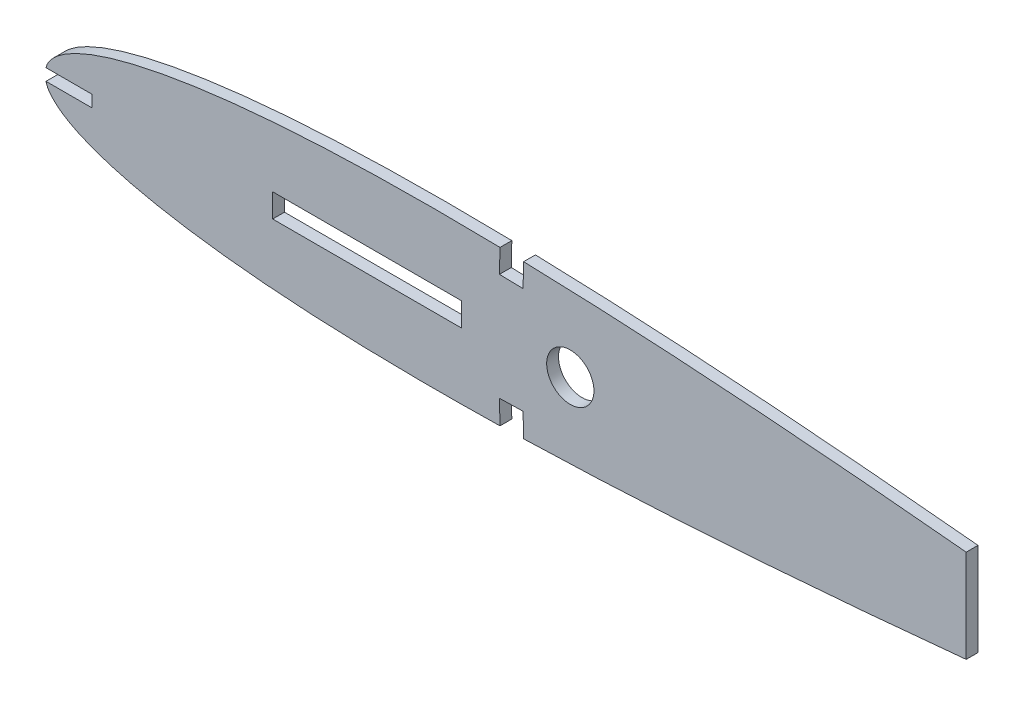
SolidWorks part; units mm, degrees
material "Balsa"
ref_plane "Front Plane" through (0, 0, 0) normal (0, 0, 1) x (1, 0, 0)
ref_plane "Top Plane" through (0, 0, 0) normal (0, 1, 0) x (1, 0, 0)
ref_plane "Right Plane" through (0, 0, 0) normal (1, 0, 0) x (0, 0, -1)
curve "Curve1"
  spline degree 3 poles (318.77, 0, 0) (318.6165, 0.178, 0) (318.1279, 0.7447, 0) (316.4159, 0.5798, 0) (314.0794, 1.1239, 0) (310.6457, 1.4976, 0) (306.3402, 2.1168, 0) (301.1057, 2.7975, 0) (295.0055, 3.5941, 0) (288.0665, 4.472, 0) (280.335, 5.4268, 0) (271.8575, 6.4421, 0) (262.6867, 7.5062, 0) (252.8789, 8.6045, 0) (242.4947, 9.7236, 0) (231.5982, 10.8496, 0) (220.2564, 11.9679, 0) (208.5394, 13.0629, 0) (196.5193, 14.1202, 0) (184.2704, 15.122, 0) (171.8679, 16.0521, 0) (159.3884, 16.8933, 0) (146.9087, 17.6278, 0) (134.5058, 18.2372, 0) (122.2562, 18.7052, 0) (110.2351, 19.0165, 0) (98.5168, 19.156, 0) (87.1732, 19.1125, 0) (76.2743, 18.8777, 0) (65.8873, 18.4456, 0) (56.076, 17.8151, 0) (46.9007, 16.9881, 0) (38.4176, 15.971, 0) (30.6784, 14.7725, 0) (23.7299, 13.4051, 0) (17.6134, 11.8842, 0) (12.3615, 10.2248, 0) (8.0073, 8.4423, 0) (4.5466, 6.5486, 0) (2.0351, 4.5401, 0) (0.333, 2.3682, 0) (0.1059, 0.7528, 0) (0, 0, 0) knots 0 0 0 0 0.002092 0.00666 0.01424 0.024785 0.038227 0.054481 0.073445 0.094999 0.119006 0.145319 0.17377 0.204184 0.236371 0.270129 0.30525 0.341517 0.378701 0.416575 0.454902 0.493447 0.531971 0.570237 0.608013 0.645066 0.681178 0.71613 0.749718 0.781748 0.812037 0.840415 0.866732 0.890849 0.912652 0.932046 0.948973 0.963413 0.975421 0.985175 0.993091 1 1 1 1
sketch "Sketch2" plane through (0, 0, 0) normal (0, 0, 1) x (1, 0, 0)
  line L4 (0, 0) -> (349.25, 0) construction
  spline S1 degree 3 poles (349.25, 0) (349.0818, 0.195) (348.5465, 0.8159) (346.6708, 0.6353) (344.1109, 1.2313) (340.3489, 1.6408) (335.6317, 2.3192) (329.8967, 3.065) (323.2132, 3.9378) (315.6107, 4.8996) (307.1399, 5.9457) (297.8518, 7.058) (287.8042, 8.224) (277.0586, 9.4273) (265.6815, 10.6534) (253.743, 11.887) (241.3168, 13.1123) (228.4795, 14.3119) (215.31, 15.4703) (201.8899, 16.5679) (188.3015, 17.587) (174.6287, 18.5086) (160.9558, 19.3133) (147.3669, 19.981) (133.9461, 20.4937) (120.7755, 20.8348) (107.9367, 20.9876) (95.5085, 20.94) (83.5675, 20.6828) (72.1873, 20.2093) (61.4378, 19.5185) (51.3852, 18.6124) (42.091, 17.4981) (33.6118, 16.185) (25.9989, 14.6868) (19.2975, 13.0206) (13.5435, 11.2025) (8.7729, 9.2495) (4.9814, 7.1748) (2.2297, 4.9742) (0.3649, 2.5947) (0.116, 0.8248) (0, 0) knots 0 0 0 0 0.002092 0.00666 0.01424 0.024785 0.038227 0.054481 0.073445 0.094999 0.119006 0.145319 0.17377 0.204184 0.236371 0.270129 0.30525 0.341517 0.378701 0.416575 0.454902 0.493447 0.531971 0.570237 0.608013 0.645066 0.681178 0.71613 0.749718 0.781748 0.812037 0.840415 0.866732 0.890849 0.912652 0.932046 0.948973 0.963413 0.975421 0.985175 0.993091 1 1 1 1
  spline S2 degree 3 poles (349.25, 0) (349.0818, -0.195) (348.5465, -0.8159) (346.6708, -0.6353) (344.1109, -1.2313) (340.3489, -1.6408) (335.6317, -2.3192) (329.8967, -3.065) (323.2132, -3.9378) (315.6107, -4.8996) (307.1399, -5.9457) (297.8518, -7.058) (287.8042, -8.224) (277.0586, -9.4273) (265.6815, -10.6534) (253.743, -11.887) (241.3168, -13.1123) (228.4795, -14.3119) (215.31, -15.4703) (201.8899, -16.5679) (188.3015, -17.587) (174.6287, -18.5086) (160.9558, -19.3133) (147.3669, -19.981) (133.9461, -20.4937) (120.7755, -20.8348) (107.9367, -20.9876) (95.5085, -20.94) (83.5675, -20.6828) (72.1873, -20.2093) (61.4378, -19.5185) (51.3852, -18.6124) (42.091, -17.4981) (33.6118, -16.185) (25.9989, -14.6868) (19.2975, -13.0206) (13.5435, -11.2025) (8.7729, -9.2495) (4.9814, -7.1748) (2.2297, -4.9742) (0.3649, -2.5947) (0.116, -0.8248) (0, 0) knots 0 0 0 0 0.002092 0.00666 0.01424 0.024785 0.038227 0.054481 0.073445 0.094999 0.119006 0.145319 0.17377 0.204184 0.236371 0.270129 0.30525 0.341517 0.378701 0.416575 0.454902 0.493447 0.531971 0.570237 0.608013 0.645066 0.681178 0.71613 0.749718 0.781748 0.812037 0.840415 0.866732 0.890849 0.912652 0.932046 0.948973 0.963413 0.975421 0.985175 0.993091 1 1 1 1
  dimension "D1" = 349.25
extrude "Boss-Extrude1" add sketch "Sketch2" along normal blind 3.175
sketch "Sketch3" plane through (0, 0, 3.175) normal (0, 0, 1) x (1, 0, 0)
  line L0 (0, 0) -> (141.224, 0) construction
  line L1 (349.25, 50.8) -> (247.65, 50.8)
  line L2 (349.25, 50.8) -> (349.25, -50.8)
  line L3 (349.25, -50.8) -> (247.65, -50.8)
  line L4 (247.65, 50.8) -> (247.65, -50.8)
  line L5 (0, 1.5875) -> (12.7, 1.5875)
  line L6 (0, 1.5875) -> (0, -1.5875)
  line L7 (0, -1.5875) -> (12.7, -1.5875)
  line L8 (12.7, 1.5875) -> (12.7, -1.5875)
  line L9 (128.6754, -20.6224) -> (128.524, -14.2742)
  line L10 (128.6754, -20.6224) -> (122.3272, -20.7738) construction
  line L11 (128.524, -14.2742) -> (122.1758, -14.4256)
  line L12 (122.3272, -20.7738) -> (122.1758, -14.4256)
  line L13 (122.3272, -20.7738) -> (128.6754, -20.6224) construction
  line L14 (122.3272, -20.7738) -> (122.6301, -33.4702)
  line L15 (128.6754, -20.6224) -> (128.9783, -33.3188)
  line L16 (122.6301, -33.4702) -> (128.9783, -33.3188)
  line L17 (128.524, 14.2742) -> (122.1758, 14.4256)
  line L18 (128.524, 14.2742) -> (128.6754, 20.6224)
  line L19 (122.1758, 14.4256) -> (122.3272, 20.7738)
  line L20 (128.6754, 20.6224) -> (122.3272, 20.7738) construction
  line L21 (122.3272, 20.7738) -> (128.6754, 20.6224) construction
  line L22 (122.3272, 20.7738) -> (122.5522, 30.2059)
  line L23 (128.6754, 20.6224) -> (128.9004, 30.0545)
  line L24 (122.5522, 30.2059) -> (128.9004, 30.0545)
  circle A0 centre (141.224, 0) radius 6.35
  spline S0 degree 3 poles (0, 0) (0.116, -0.8248) (0.3649, -2.5947) (2.2297, -4.9742) (4.9814, -7.1748) (8.7729, -9.2495) (13.5435, -11.2025) (19.2975, -13.0206) (25.9989, -14.6868) (33.6118, -16.185) (42.091, -17.4981) (51.3852, -18.6124) (61.4378, -19.5185) (72.1873, -20.2093) (83.5675, -20.6828) (95.5085, -20.94) (107.9367, -20.9876) (120.7755, -20.8348) (133.9461, -20.4937) (147.3669, -19.981) (160.9558, -19.3133) (174.6287, -18.5086) (188.3015, -17.587) (201.8899, -16.5679) (215.31, -15.4703) (228.4795, -14.3119) (241.3168, -13.1123) (253.743, -11.887) (265.6815, -10.6534) (277.0586, -9.4273) (287.8042, -8.224) (297.8518, -7.058) (307.1399, -5.9457) (315.6107, -4.8996) (323.2132, -3.9378) (329.8967, -3.065) (335.6317, -2.3192) (340.3489, -1.6408) (344.1109, -1.2313) (346.6708, -0.6353) (348.5465, -0.8159) (349.0818, -0.195) (349.25, 0) knots 0 0 0 0 0.006909 0.014825 0.024579 0.036587 0.051027 0.067954 0.087348 0.109151 0.133268 0.159585 0.187963 0.218252 0.250282 0.28387 0.318822 0.354934 0.391987 0.429763 0.468029 0.506553 0.545098 0.583425 0.621299 0.658483 0.69475 0.729871 0.763629 0.795816 0.82623 0.854681 0.880994 0.905001 0.926555 0.945519 0.961773 0.975215 0.98576 0.99334 0.997908 1 1 1 1 construction
  spline S1 degree 3 poles (349.25, 0) (349.0818, 0.195) (348.5465, 0.8159) (346.6708, 0.6353) (344.1109, 1.2313) (340.3489, 1.6408) (335.6317, 2.3192) (329.8967, 3.065) (323.2132, 3.9378) (315.6107, 4.8996) (307.1399, 5.9457) (297.8518, 7.058) (287.8042, 8.224) (277.0586, 9.4273) (265.6815, 10.6534) (253.743, 11.887) (241.3168, 13.1123) (228.4795, 14.3119) (215.31, 15.4703) (201.8899, 16.5679) (188.3015, 17.587) (174.6287, 18.5086) (160.9558, 19.3133) (147.3669, 19.981) (133.9461, 20.4937) (120.7755, 20.8348) (107.9367, 20.9876) (95.5085, 20.94) (83.5675, 20.6828) (72.1873, 20.2093) (61.4378, 19.5185) (51.3852, 18.6124) (42.091, 17.4981) (33.6118, 16.185) (25.9989, 14.6868) (19.2975, 13.0206) (13.5435, 11.2025) (8.7729, 9.2495) (4.9814, 7.1748) (2.2297, 4.9742) (0.3649, 2.5947) (0.116, 0.8248) (0, 0) knots 0 0 0 0 0.002092 0.00666 0.01424 0.024785 0.038227 0.054481 0.073445 0.094999 0.119006 0.145319 0.17377 0.204184 0.236371 0.270129 0.30525 0.341517 0.378701 0.416575 0.454902 0.493447 0.531971 0.570237 0.608013 0.645066 0.681178 0.71613 0.749718 0.781748 0.812037 0.840415 0.866732 0.890849 0.912652 0.932046 0.948973 0.963413 0.975421 0.985175 0.993091 1 1 1 1 construction
  dimension "D5" = 12.7
  dimension "D1" = 12.7
  dimension "D2" = 3.175
  dimension "D3" = 101.6
  dimension "D4" = 101.6
  dimension "D6" = 208.026
  dimension "D7" = 6.35
  dimension "D8" = 6.35
  dimension "D9" = 12.7
  dimension "D10" = 12.7
  dimension "D11" = 6.35
  dimension "D12" = 6.35
  dimension "D13" = 9.4321
extrude "Cut-Extrude1" cut sketch "Sketch3" against normal blind 5.08
sketch "Sketch4" plane through (0, 0, 3.175) normal (0, 0, 1) x (1, 0, 0)
  line L1 (61.214, 3.175) -> (112.014, 3.175)
  line L2 (61.214, 3.175) -> (61.214, -3.175)
  line L3 (61.214, -3.175) -> (112.014, -3.175)
  line L4 (112.014, 3.175) -> (112.014, -3.175)
  circle A1 centre (141.224, 0) radius 6.35 construction
  point P4 (0, 0)
  dimension "D2" = 50.8
  dimension "D4" = 29.21
  dimension "D1" = 6.35
  dimension "D3" = 3.175
extrude "Cut-Extrude2" cut sketch "Sketch4" against normal blind 5.08
